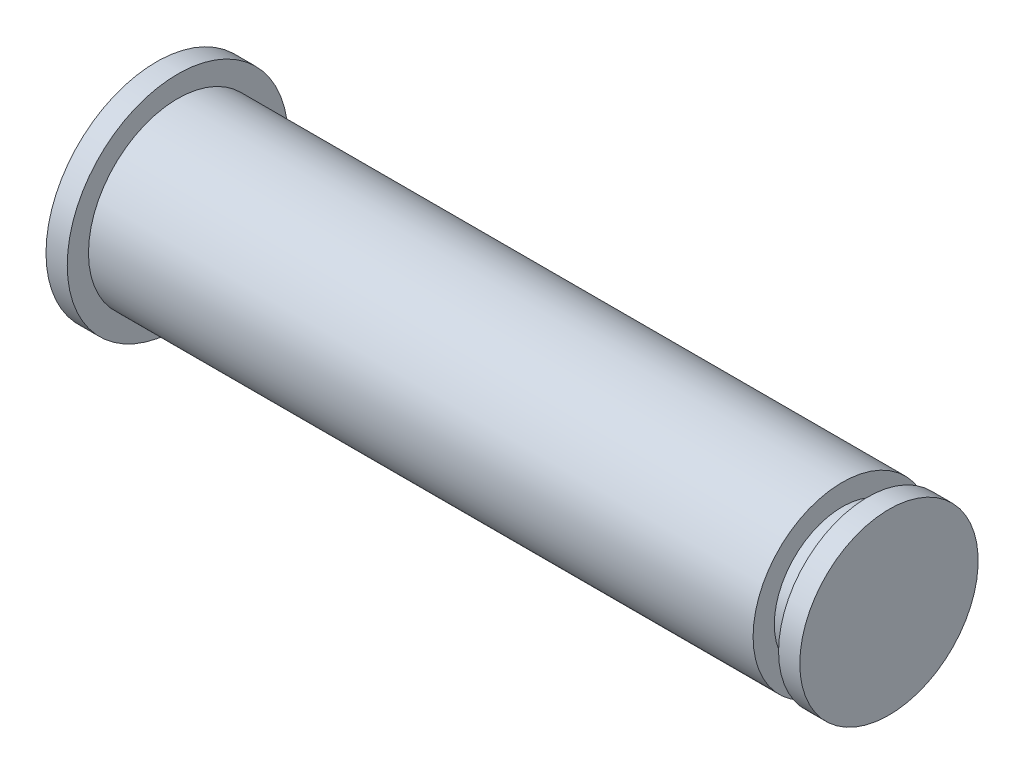
SolidWorks part; units mm, degrees
material "6061 合金"
ref_plane "前视基准面" through (0, 0, 0) normal (0, 0, 1) x (1, 0, 0)
ref_plane "上视基准面" through (0, 0, 0) normal (0, 1, 0) x (1, 0, 0)
ref_plane "右视基准面" through (0, 0, 0) normal (1, 0, 0) x (0, 0, -1)
sketch "草图1" plane through (0, 0, 0) normal (0, 0, 1) x (1, 0, 0)
  line L1 (32.3, 4.2) -> (1, 4.2)
  line L2 (0, 0) -> (34.5, 0)
  line L3 (0, 0) -> (0, 5.2)
  line L4 (0, 5.2) -> (1, 5.2)
  line L5 (34.5, 0) -> (34.5, 4.2)
  line L8 (34.5, 4.2) -> (33.5, 4.2)
  line L9 (1, 5.2) -> (1, 4.2)
  line L11 (32.3, 4.2) -> (32.3, 3.2)
  line L12 (32.3, 3.2) -> (33.5, 3.2)
  line L13 (33.5, 4.2) -> (33.5, 3.2)
  dimension "D1" = 1
  dimension "D2" = 34.5
  dimension "D3" = 1.2
  dimension "D4" = 1
  dimension "D5" = 1
  dimension "D6" = 4.2
  dimension "D7" = 1
revolve "旋转1" add sketch "草图1" angle 360 about L2
